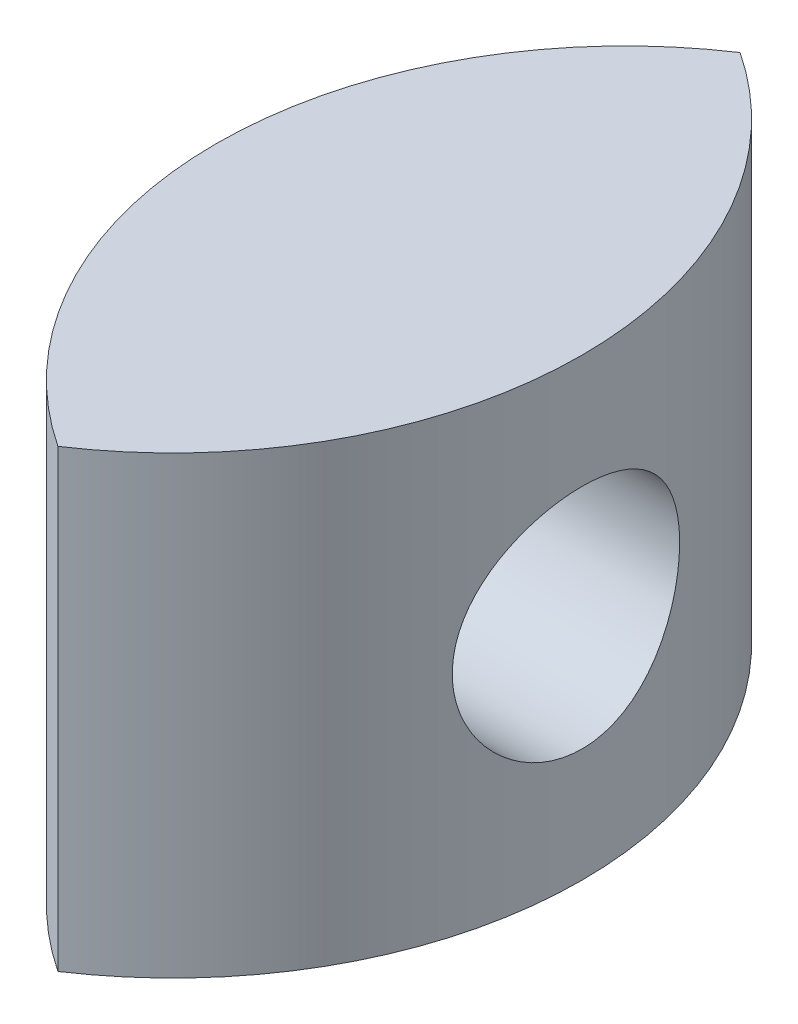
SolidWorks part; units mm, degrees
ref_plane "Front Plane" through (0, 0, 0) normal (0, 0, 1) x (1, 0, 0)
ref_plane "Top Plane" through (0, 0, 0) normal (0, 1, 0) x (1, 0, 0)
ref_plane "Right Plane" through (0, 0, 0) normal (1, 0, 0) x (0, 0, -1)
sketch "Sketch1" plane through (0, 0, 0) normal (0, 1, 0) x (1, 0, 0)
  line L0 (0, 75) -> (0, -75) construction
  arc A0 (0, 75) -> (0, -75) centre (49.7494, 0) ccw
  arc A1 (0, 75) -> (0, -75) centre (-49.7494, 0) cw
  dimension "D2" = 90
  dimension "D1" = 150
extrude "Boss-Extrude1" add sketch "Sketch1" along normal blind 100
sketch "Sketch2" plane through (0, 0, 0) normal (1, 0, 0) x (0, 0, -1)
  line L0 (0, 100) -> (0, 0) construction
  line L1 (75, 100) -> (-75, 100) construction
  circle A0 centre (0, 50) radius 25
  point P2 (0, 0)
  dimension "D1" = 50
extrude "Cut-Extrude1" cut sketch "Sketch2" against normal through all both and the other way through all
